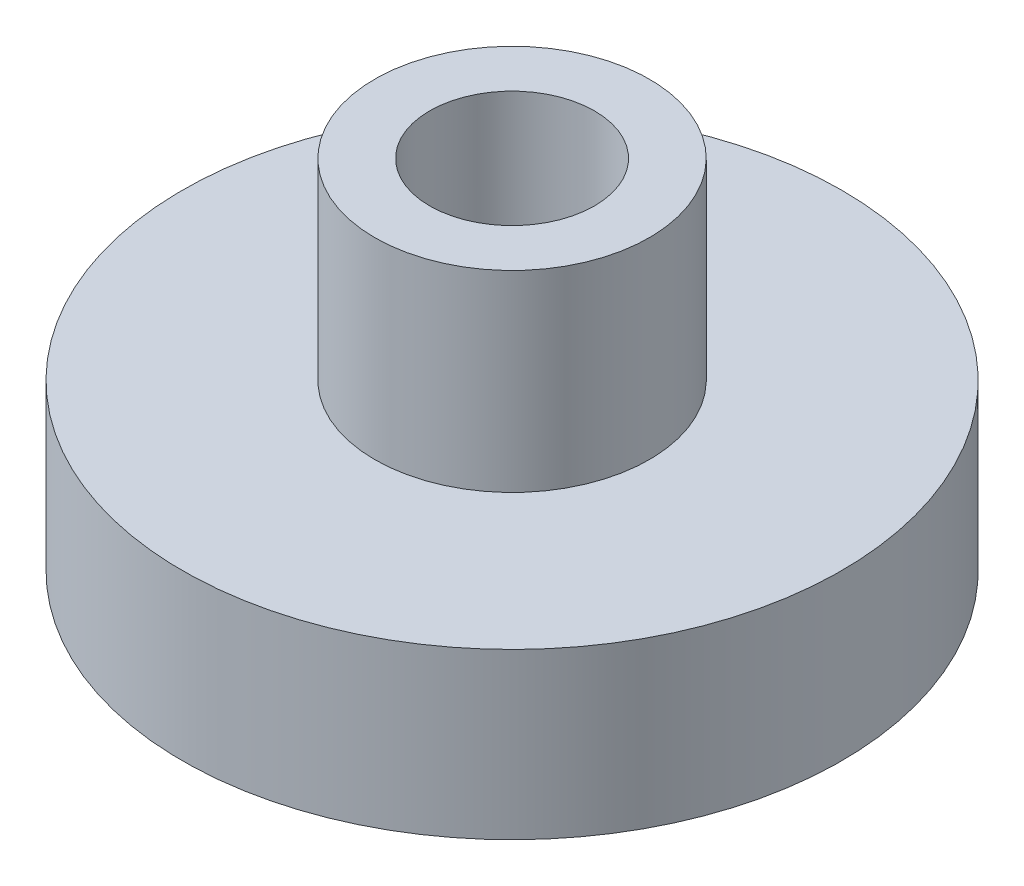
SolidWorks part; units mm, degrees
ref_plane "前视基准面" through (0, 0, 0) normal (0, 0, 1) x (1, 0, 0)
ref_plane "上视基准面" through (0, 0, 0) normal (0, 1, 0) x (1, 0, 0)
ref_plane "右视基准面" through (0, 0, 0) normal (1, 0, 0) x (0, 0, -1)
other "Configuration Table"
sketch "草图1" plane through (0, 0, 0) normal (0, 1, 0) x (1, 0, 0)
  circle A0 centre (0, 0) radius 2.5
  circle A1 centre (0, 0) radius 1.5
  dimension "D1" = 3
  dimension "D2" = 5
extrude "凸台-拉伸1" add sketch "草图1" along normal blind 3.5
sketch "草图2" plane through (0, 0, 0) normal (0, -1, 0) x (1, 0, 0)
  circle A0 centre (0, 0) radius 1.5
  circle A1 centre (0, 0) radius 6
  dimension "D1" = 3
  dimension "D2" = 12
extrude "凸台-拉伸2" add sketch "草图2" along normal blind 3
